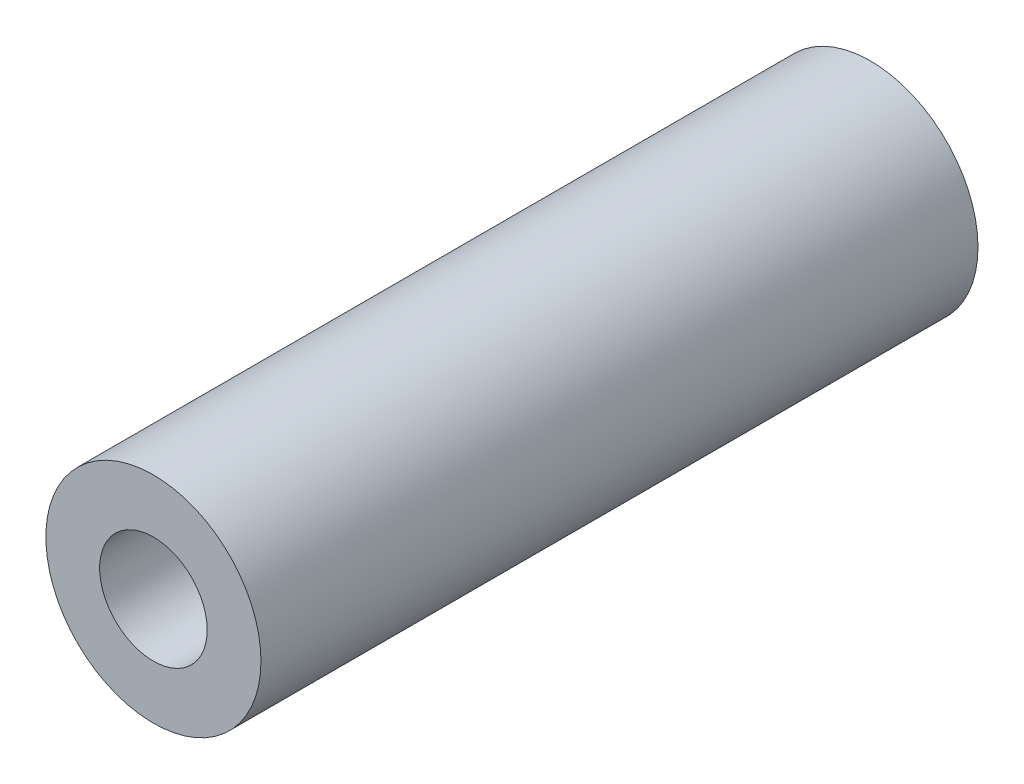
SolidWorks part; units mm, degrees
ref_plane "Front Plane" through (0, 0, 0) normal (0, 0, 1) x (1, 0, 0)
ref_plane "Top Plane" through (0, 0, 0) normal (0, 1, 0) x (1, 0, 0)
ref_plane "Right Plane" through (0, 0, 0) normal (1, 0, 0) x (0, 0, -1)
sketch "Sketch1" plane through (0, 0, 0) normal (0, 0, 1) x (1, 0, 0)
  circle A0 centre (0, 0) radius 3
  dimension "D1" = 6
extrude "Boss-Extrude1" add sketch "Sketch1" along normal blind 20
sketch "Sketch2" plane through (0, 0, 20) normal (0, 0, 1) x (1, 0, 0)
  line L0 (0, 1.5) -> (0, 3)
  circle A0 centre (0, 0) radius 1.5
  circle A1 centre (0, 0) radius 3 construction
  dimension "D1" = 3
extrude "Cut-Extrude1" cut sketch "Sketch2" against normal blind 3 contours A0
sketch "Sketch3" plane through (0, 0, 0) normal (0, 0, -1) x (-1, 0, 0)
  circle A0 centre (0, 0) radius 1.5
  dimension "D1" = 3
extrude "Cut-Extrude2" cut sketch "Sketch3" against normal blind 3 contours A0
